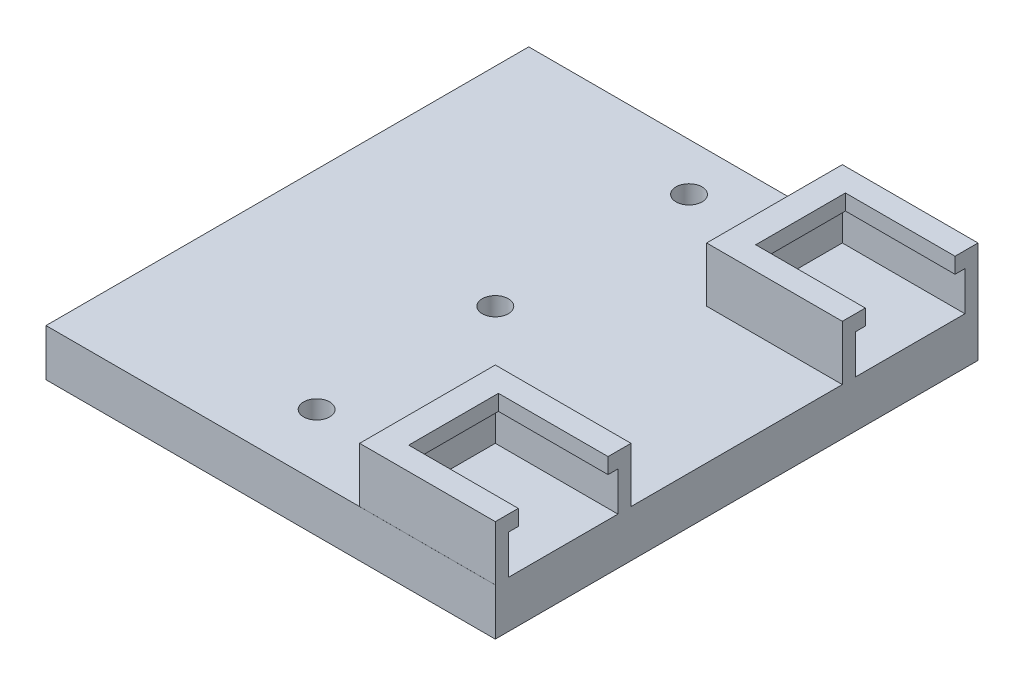
SolidWorks part; units mm, degrees
ref_plane "Front Plane" through (0, 0, 0) normal (0, 0, 1) x (1, 0, 0)
ref_plane "Top Plane" through (0, 0, 0) normal (0, 1, 0) x (1, 0, 0)
ref_plane "Right Plane" through (0, 0, 0) normal (1, 0, 0) x (0, 0, -1)
sketch "Sketch1" plane through (0, 0, 0) normal (0, 1, 0) x (1, 0, 0)
  line L1 (-66.5, -66.5) -> (66.5, -66.5)
  line L2 (-66.5, -66.5) -> (-66.5, 66.5)
  line L3 (-66.5, 66.5) -> (66.5, 66.5)
  line L4 (66.5, -66.5) -> (66.5, 66.5)
  line L5 (-66.5, -66.5) -> (66.5, 66.5) construction
  line L6 (-66.5, 66.5) -> (66.5, -66.5) construction
  point P0 (0, 0)
extrude "Boss-Extrude2" add sketch "Sketch1" along normal blind 136
sketch "Sketch2" plane through (0, 0, 66.5) normal (0, 0, 1) x (1, 0, 0)
  line L0 (66.5, 136) -> (66.5, 0) construction
  line L1 (-66.5, 136) -> (66.5, 136)
  line L2 (-66.5, 136) -> (-66.5, 127)
  line L3 (-66.5, 127) -> (66.5, 127)
  line L4 (66.5, 136) -> (66.5, 127)
  line L6 (-66.5, 0) -> (66.5, 0)
  line L7 (-66.5, 0) -> (-66.5, 9)
  line L8 (-66.5, 9) -> (66.5, 9)
  line L9 (66.5, 0) -> (66.5, 9)
  line L10 (-66.5, 127) -> (66.5, 127)
  line L11 (-66.5, 127) -> (-66.5, 9)
  line L12 (-66.5, 9) -> (66.5, 9)
  line L13 (66.5, 127) -> (66.5, 9)
  line M2 (66.5, 0) -> (66.5, 136)
  line M4 (-66.5, 136) -> (-66.5, 0)
extrude "Cut-Extrude1" cut sketch "Sketch2" against normal blind 136 contours L8 L3 M4 M2
sketch "Sketch4" plane through (0, 9, 0) normal (0, 1, 0) x (1, 0, 0)
  line L0 (0, 66.5) -> (0, -66.5) construction
  line L1 (-66.5, 66.5) -> (66.5, 66.5) construction
  line L2 (-66.5, -66.5) -> (66.5, -66.5) construction
  line L3 (0, -66.5) -> (33.25, -66.5) construction
  line L4 (33.25, -66.5) -> (33.25, 66.5) construction
  line L5 (0, 0) -> (66.5, 0) construction
  line L6 (66.5, 66.5) -> (66.5, -66.5) construction
  line L7 (66.5, 0) -> (66.5, 33.25) construction
  line L8 (66.5, 33.25) -> (0, 33.25) construction
  line L9 (0, 33.25) -> (0, -33.25) construction
  line L10 (0, -33.25) -> (66.5, -33.25) construction
  line L11 (43.75, 43.75) -> (22.75, 43.75)
  line L12 (43.75, -22.75) -> (22.75, -22.75)
  line L13 (43.75, -22.75) -> (43.75, -43.75)
  line L14 (43.75, -43.75) -> (22.75, -43.75)
  line L15 (22.75, -22.75) -> (22.75, -43.75)
  line L16 (43.75, -22.75) -> (22.75, -43.75) construction
  line L17 (43.75, -43.75) -> (22.75, -22.75) construction
  line L18 (46.25, -20.25) -> (20.25, -20.25)
  line L19 (46.25, -20.25) -> (46.25, -46.25)
  line L20 (46.25, -46.25) -> (20.25, -46.25)
  line L21 (20.25, -20.25) -> (20.25, -46.25)
  line L22 (46.25, -20.25) -> (20.25, -46.25) construction
  line L23 (46.25, -46.25) -> (20.25, -20.25) construction
  line L24 (22.75, 22.75) -> (22.75, 43.75)
  line L25 (43.75, 22.75) -> (22.75, 22.75)
  line L26 (43.75, 22.75) -> (43.75, 43.75)
  line L27 (46.25, 46.25) -> (20.25, 46.25)
  line L28 (20.25, 20.25) -> (20.25, 46.25)
  line L29 (46.25, 20.25) -> (20.25, 20.25)
  line L30 (46.25, 20.25) -> (46.25, 46.25)
  line L31 (46.25, 46.25) -> (20.25, 20.25) construction
  line L32 (46.25, 20.25) -> (20.25, 46.25) construction
  line L34 (43.75, -43.75) -> (46.25, -43.75)
  line L35 (43.75, -43.75) -> (43.75, -22.75)
  line L36 (43.75, -22.75) -> (46.25, -22.75)
  line L37 (46.25, -43.75) -> (46.25, -22.75)
  line L38 (43.75, 22.75) -> (46.25, 22.75)
  line L39 (43.75, 22.75) -> (43.75, 43.75)
  line L40 (43.75, 43.75) -> (46.25, 43.75)
  line L41 (46.25, 22.75) -> (46.25, 43.75)
  point P18 (33.25, -33.25)
  point P23 (33.25, -33.25)
  point P36 (33.25, 33.25)
extrude "Boss-Extrude3" add sketch "Sketch4" along normal blind 10.5 contours L12 L36 L19 L18 L21 L20 L34 L14 L15 | L11 L40 L30 L27 L28 L29 L38 L25 L24
sketch "Sketch5" plane through (22.75, 0, 0) normal (1, 0, 0) x (0, 0, -1)
  line L0 (-22.75, 19.5) -> (-22.75, 9) construction
  line L1 (-43.75, 19.5) -> (-22.75, 19.5)
  line L2 (-43.75, 19.5) -> (-43.75, 16.5)
  line L3 (-43.75, 16.5) -> (-22.75, 16.5)
  line L4 (-22.75, 19.5) -> (-22.75, 16.5)
  line L5 (43.75, 19.5) -> (43.75, 9) construction
  line L6 (22.75, 19.5) -> (43.75, 19.5)
  line L7 (22.75, 19.5) -> (22.75, 16.5)
  line L8 (22.75, 16.5) -> (43.75, 16.5)
  line L9 (43.75, 19.5) -> (43.75, 16.5)
extrude "Boss-Extrude4" add sketch "Sketch5" along normal up to surface (23.5 mm away) up to face at (46.25, 14.25, 45)
sketch "Sketch6" plane through (0, 19.5, 0) normal (0, 1, 0) x (1, 0, 0)
  line L0 (46.25, -46.25) -> (46.25, -20.25) construction
  line L1 (46.25, 20.25) -> (46.25, 46.25) construction
  line L2 (67.25, -41.85) -> (25.25, -41.85)
  line L3 (67.25, -41.85) -> (67.25, -24.65)
  line L4 (67.25, -24.65) -> (25.25, -24.65)
  line L5 (25.25, -41.85) -> (25.25, -24.65)
  line L6 (67.25, -41.85) -> (25.25, -24.65) construction
  line L7 (67.25, -24.65) -> (25.25, -41.85) construction
  line L9 (67.25, 24.65) -> (25.25, 24.65)
  line L10 (67.25, 24.65) -> (67.25, 41.85)
  line L11 (67.25, 41.85) -> (25.25, 41.85)
  line L12 (25.25, 24.65) -> (25.25, 41.85)
  line L13 (67.25, 24.65) -> (25.25, 41.85) construction
  line L14 (67.25, 41.85) -> (25.25, 24.65) construction
  point P4 (46.25, -33.25)
  point P13 (46.25, 33.25)
extrude "Cut-Extrude2" cut sketch "Sketch6" against normal up to surface (3 mm away) up to face at (34.5, 16.5, -33.25)
sketch "Sketch7" plane through (0, 127, 0) normal (0, -1, 0) x (1, 0, 0)
  line L0 (0, 66.5) -> (0, -66.5) construction
  line L1 (-66.5, 66.5) -> (66.5, 66.5) construction
  line L2 (-66.5, -66.5) -> (66.5, -66.5) construction
  line L3 (0, -66.5) -> (-33.25, -66.5) construction
  line L4 (-33.25, -66.5) -> (-33.25, 66.5) construction
  line L5 (-33.25, 66.5) -> (-66.5, 66.5) construction
  line L6 (-66.5, 66.5) -> (-66.5, 0) construction
  line L8 (-66.5, 0) -> (0, 0) construction
  line L9 (0, 0) -> (0, -33.25) construction
  line L10 (0, -33.25) -> (-66.5, -33.25) construction
  line L11 (-66.5, -66.5) -> (-66.5, 66.5) construction
  line L12 (-66.5, -33.25) -> (-66.5, 33.25) construction
  line L13 (-66.5, 33.25) -> (0, 33.25) construction
  line L14 (-22.75, -22.75) -> (-43.75, -22.75)
  line L15 (-22.75, 43.75) -> (-43.75, 43.75)
  line L16 (-22.75, 43.75) -> (-22.75, 22.75)
  line L17 (-22.75, 22.75) -> (-43.75, 22.75)
  line L18 (-43.75, 43.75) -> (-43.75, 22.75)
  line L19 (-22.75, 43.75) -> (-43.75, 22.75) construction
  line L20 (-22.75, 22.75) -> (-43.75, 43.75) construction
  line L21 (-20.25, 46.25) -> (-46.25, 46.25)
  line L22 (-20.25, 46.25) -> (-20.25, 20.25)
  line L23 (-20.25, 20.25) -> (-46.25, 20.25)
  line L24 (-46.25, 46.25) -> (-46.25, 20.25)
  line L25 (-20.25, 46.25) -> (-46.25, 20.25) construction
  line L26 (-20.25, 20.25) -> (-46.25, 46.25) construction
  line L27 (-43.75, -43.75) -> (-43.75, -22.75)
  line L28 (-22.75, -43.75) -> (-43.75, -43.75)
  line L29 (-22.75, -43.75) -> (-22.75, -22.75)
  line L30 (-20.25, -20.25) -> (-46.25, -20.25)
  line L31 (-46.25, -46.25) -> (-46.25, -20.25)
  line L32 (-20.25, -46.25) -> (-46.25, -46.25)
  line L33 (-20.25, -46.25) -> (-20.25, -20.25)
  line L34 (-20.25, -20.25) -> (-46.25, -46.25) construction
  line L35 (-20.25, -46.25) -> (-46.25, -20.25) construction
  line L36 (-43.75, -22.75) -> (-46.25, -22.75)
  line L37 (-43.75, 43.75) -> (-46.25, 43.75)
  line L38 (-43.75, 43.75) -> (-43.75, 22.75)
  line L39 (-43.75, 22.75) -> (-46.25, 22.75)
  line L40 (-46.25, 43.75) -> (-46.25, 22.75)
  line L41 (-46.25, -43.75) -> (-46.25, -22.75)
  line L42 (-43.75, -43.75) -> (-46.25, -43.75)
  line L43 (-43.75, -43.75) -> (-43.75, -22.75)
  point P17 (-33.25, 33.25)
  point P24 (-33.25, 33.25)
  point P37 (-33.25, -33.25)
extrude "Boss-Extrude5" add sketch "Sketch7" along normal blind 10.5 contours L17 L39 L24 L23 L22 L21 L37 L15 L16 | L28 L42 L31 L32 L33 L30 L36 L14 L29
sketch "Sketch8" plane through (-22.75, 0, 0) normal (-1, 0, 0) x (0, 0, 1)
  line L0 (22.75, 116.5) -> (22.75, 127) construction
  line L1 (43.75, 116.5) -> (22.75, 116.5)
  line L2 (43.75, 116.5) -> (43.75, 119.5)
  line L3 (43.75, 119.5) -> (22.75, 119.5)
  line L4 (22.75, 116.5) -> (22.75, 119.5)
  line L5 (-22.75, 116.5) -> (-22.75, 127) construction
  line L6 (-43.75, 116.5) -> (-22.75, 116.5)
  line L7 (-43.75, 116.5) -> (-43.75, 119.5)
  line L8 (-43.75, 119.5) -> (-22.75, 119.5)
  line L9 (-22.75, 116.5) -> (-22.75, 119.5)
extrude "Boss-Extrude6" add sketch "Sketch8" along normal up to surface (23.5 mm away) up to face at (-46.25, 121.75, 45)
sketch "Sketch9" plane through (0, 116.5, 0) normal (0, -1, 0) x (1, 0, 0)
  line L0 (-46.25, 46.25) -> (-46.25, 20.25) construction
  line L1 (-46.25, 20.25) -> (-46.25, -20.25) construction
  line L2 (-46.25, -20.25) -> (-46.25, -46.25) construction
  line L4 (-67.25, 41.85) -> (-25.25, 41.85)
  line L5 (-67.25, 41.85) -> (-67.25, 24.65)
  line L6 (-67.25, 24.65) -> (-25.25, 24.65)
  line L7 (-25.25, 41.85) -> (-25.25, 24.65)
  line L8 (-67.25, 41.85) -> (-25.25, 24.65) construction
  line L9 (-67.25, 24.65) -> (-25.25, 41.85) construction
  line L10 (-67.25, -24.65) -> (-25.25, -24.65)
  line L11 (-67.25, -24.65) -> (-67.25, -41.85)
  line L12 (-67.25, -41.85) -> (-25.25, -41.85)
  line L13 (-25.25, -24.65) -> (-25.25, -41.85)
  line L14 (-67.25, -24.65) -> (-25.25, -41.85) construction
  line L15 (-67.25, -41.85) -> (-25.25, -24.65) construction
  point P4 (-46.25, 33.25)
  point P13 (-46.25, -33.25)
extrude "Cut-Extrude3" cut sketch "Sketch9" against normal up to surface (3 mm away) up to face at (-34.5, 119.5, 33.25)
sketch "Sketch10" plane through (0, 0, 0) normal (0, -1, 0) x (1, 0, 0)
  line L0 (-66.5, -66.5) -> (66.5, -66.5) construction
  line L1 (66.5, -66.5) -> (0, -66.5) construction
  line L2 (0, -66.5) -> (0, 66.5) construction
  line L3 (-66.5, 66.5) -> (66.5, 66.5) construction
  line L5 (-9.6307, -66.5) -> (9.6307, -66.5)
  line L6 (-9.6307, -66.5) -> (-9.6307, 66.5)
  line L7 (-9.6307, 66.5) -> (9.6307, 66.5)
  line L8 (9.6307, -66.5) -> (9.6307, 66.5)
  line L9 (-9.6307, -66.5) -> (9.6307, 66.5) construction
  line L10 (-9.6307, 66.5) -> (9.6307, -66.5) construction
  point P4 (0, 0)
extrude "Boss-Extrude7" add sketch "Sketch10" along normal blind 5
sketch "Sketch11" plane through (0, 136, 0) normal (0, 1, 0) x (1, 0, 0)
  line L0 (-66.5, -66.5) -> (66.5, -66.5) construction
  line L1 (66.5, -66.5) -> (0, -66.5) construction
  line L2 (0, -66.5) -> (0, 66.5) construction
  line L3 (66.5, 66.5) -> (-66.5, 66.5) construction
  line L4 (0, 66.5) -> (0, 0) construction
  line L6 (-9.2186, -66.5) -> (9.2186, -66.5)
  line L7 (-9.2186, -66.5) -> (-9.2186, 66.5)
  line L8 (-9.2186, 66.5) -> (9.2186, 66.5)
  line L9 (9.2186, -66.5) -> (9.2186, 66.5)
  line L10 (-9.2186, -66.5) -> (9.2186, 66.5) construction
  line L11 (-9.2186, 66.5) -> (9.2186, -66.5) construction
extrude "Boss-Extrude8" add sketch "Sketch11" along normal blind 5
sketch "Sketch12" plane through (0, 0, -66.5) normal (0, 0, -1) x (-1, 0, 0)
  line L1 (-9.6307, -5) -> (9.2186, -5)
  line L2 (-9.6307, -5) -> (-9.6307, 141)
  line L3 (-9.6307, 141) -> (9.2186, 141)
  line L4 (9.2186, -5) -> (9.2186, 141)
extrude "Boss-Extrude9" add sketch "Sketch12" along normal blind 12
sketch "Sketch14" plane through (0, 0, 66.5) normal (0, 0, 1) x (1, 0, 0)
  line L1 (-9.2186, 141) -> (9.6307, 141)
  line L2 (-9.2186, 141) -> (-9.2186, -5)
  line L3 (-9.2186, -5) -> (9.6307, -5)
  line L4 (9.6307, 141) -> (9.6307, -5)
extrude "Boss-Extrude10" add sketch "Sketch14" along normal blind 12
sketch "Sketch17" plane through (0, 0, 78.5) normal (0, 0, 1) x (1, 0, 0)
  line L0 (-9.2186, 141) -> (9.6307, -5) construction
  line L1 (9.6307, -5) -> (0.2061, 68) construction
  circle A0 centre (0.2061, 68) radius 1
extrude "Cut-Extrude4" cut sketch "Sketch17" against normal through all
sketch "Sketch20" plane through (-9.2186, 0, 0) normal (-1, 0, 0) x (0, 0, 1)
  line L0 (-78.5, 141) -> (78.5, 141) construction
  line L1 (-66.5, 136) -> (66.7446, 136)
  line L2 (-66.5, 136) -> (-66.5, 141)
  line L3 (-66.5, 141) -> (66.7446, 141)
  line L4 (66.7446, 136) -> (66.7446, 141)
extrude "Cut-Extrude10" cut sketch "Sketch20" against normal blind 19
sketch "Sketch21" plane through (-9.2186, 0, 0) normal (-1, 0, 0) x (0, 0, 1)
  line L0 (78.5, 141) -> (78.5, -5) construction
  line L1 (-78.5, 141) -> (78.5, 141)
  line L2 (-78.5, 141) -> (-78.5, 20.3342)
  line L3 (-78.5, 20.3342) -> (78.5, 20.3342)
  line L4 (78.5, 141) -> (78.5, 20.3342)
extrude "Cut-Extrude11" cut sketch "Sketch21" against normal blind 118
sketch "Sketch22" plane through (-66.5, 0, 0) normal (-1, 0, 0) x (0, 0, 1)
  line L1 (-72.3811, 141.6622) -> (113.7932, 141.6622)
  line L2 (-72.3811, 141.6622) -> (-72.3811, 99.4099)
  line L3 (-72.3811, 99.4099) -> (113.7932, 99.4099)
  line L4 (113.7932, 141.6622) -> (113.7932, 99.4099)
extrude "Cut-Extrude12" cut sketch "Sketch22" against normal blind 118
sketch "Sketch23" plane through (-9.2186, 0, 0) normal (-1, 0, 0) x (0, 0, 1)
  line L1 (-78.5, 20.3342) -> (-66.5, 20.3342)
  line L2 (-78.5, 20.3342) -> (-78.5, -5)
  line L3 (-78.5, -5) -> (-66.5, -5)
  line L4 (-66.5, 20.3342) -> (-66.5, -5)
extrude "Cut-Extrude13" cut sketch "Sketch23" against normal blind 118
sketch "Sketch24" plane through (-9.2186, 0, 0) normal (-1, 0, 0) x (0, 0, 1)
  line L1 (66.5, 20.3342) -> (78.5, 20.3342)
  line L2 (66.5, 20.3342) -> (66.5, -5)
  line L3 (66.5, -5) -> (78.5, -5)
  line L4 (78.5, 20.3342) -> (78.5, -5)
extrude "Cut-Extrude14" cut sketch "Sketch24" against normal blind 118
sketch "Sketch31" plane through (0, -5, 0) normal (0, -1, 0) x (1, 0, 0)
  circle A0 centre (0, 59.4995) radius 2.5
extrude "Cut-Extrude21" cut sketch "Sketch31" against normal blind 118
sketch "Sketch32" plane through (0, -5, 0) normal (0, -1, 0) x (1, 0, 0)
  line L0 (-66.5, -66.5) -> (66.5, -66.5) construction
  circle A0 centre (0, -59.1598) radius 2.5
  dimension "D1" = 7.3402
extrude "Cut-Extrude22" cut sketch "Sketch32" against normal blind 118
sketch "Sketch33" plane through (-9.6307, 0, 0) normal (-1, 0, 0) x (0, 0, 1)
  line L1 (-66.5, -5) -> (66.5, -5)
  line L2 (-66.5, -5) -> (-66.5, 0)
  line L3 (-66.5, 0) -> (66.5, 0)
  line L4 (66.5, -5) -> (66.5, 0)
extrude "Cut-Extrude24" cut sketch "Sketch33" against normal blind 118
sketch "Sketch34" plane through (0, 9, 0) normal (0, 1, 0) x (1, 0, 0)
  circle A0 centre (0, 0) radius 2.5
extrude "Cut-Extrude25" cut sketch "Sketch34" against normal blind 118
sketch "Sketch35" plane through (0, 9, 0) normal (0, 1, 0) x (1, 0, 0)
  line L1 (46.25, 46.25) -> (-39.847, 46.25)
  line L2 (46.25, 46.25) -> (46.25, -46.258)
  line L3 (46.25, -46.258) -> (-39.847, -46.258)
  line L4 (-39.847, 46.25) -> (-39.847, -46.258)
  line L5 (-66.5, -66.5) -> (66.5, -66.5)
  line L6 (-66.5, -66.5) -> (-66.5, 66.5)
  line L7 (-66.5, 66.5) -> (66.5, 66.5)
  line L8 (66.5, -66.5) -> (66.5, 66.5)
extrude "Cut-Extrude27" cut sketch "Sketch35" against normal blind 10
sketch "Sketch36" plane through (0, 9, 0) normal (0, 1, 0) x (1, 0, 0)
  circle A0 centre (0, 37.1264) radius 2.5
extrude "Cut-Extrude28" cut sketch "Sketch36" against normal blind 178
sketch "Sketch37" plane through (0, 9, 0) normal (0, 1, 0) x (1, 0, 0)
  circle A0 centre (0, -34.2453) radius 2.5
extrude "Cut-Extrude29" cut sketch "Sketch37" against normal blind 42
